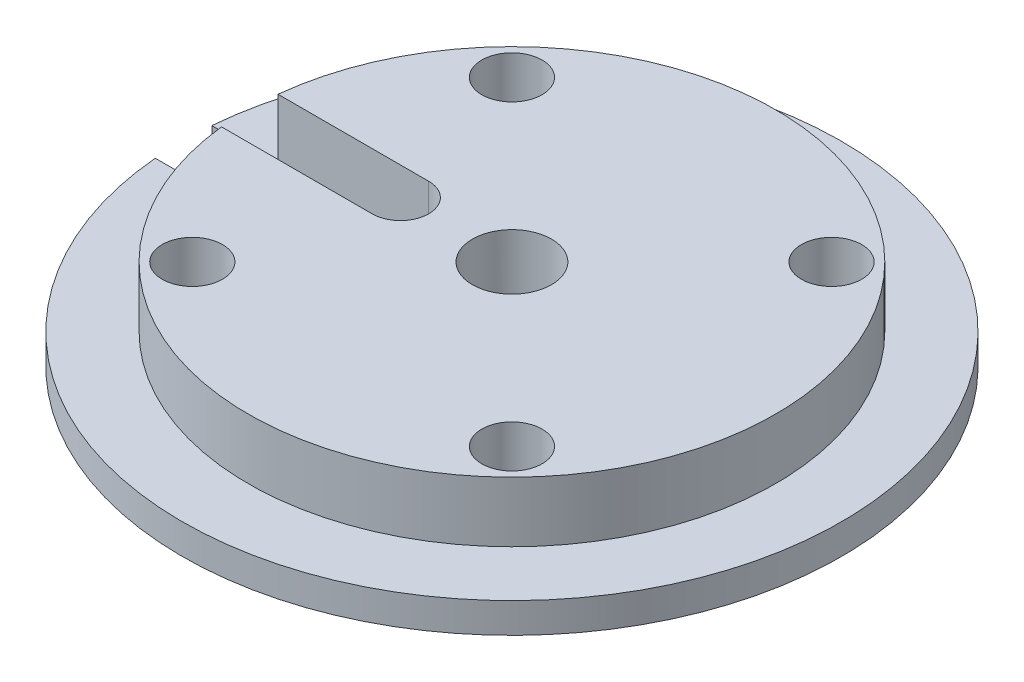
SolidWorks part; units mm, degrees
material "ABS"
ref_plane "正面" through (0, 0, 0) normal (0, 0, 1) x (1, 0, 0)
ref_plane "平面" through (0, 0, 0) normal (0, 1, 0) x (1, 0, 0)
ref_plane "右側面" through (0, 0, 0) normal (1, 0, 0) x (0, 0, -1)
sketch "ｽｹｯﾁ1" plane through (0, 0, 0) normal (0, 1, 0) x (1, 0, 0)
  circle A0 centre (0, 0) radius 2.1
  circle A1 centre (0, 0) radius 14
  dimension "D1" = 28
  dimension "D2" = 4.2
extrude "ﾎﾞｽ - 押し出し1" add sketch "ｽｹｯﾁ1" along normal blind 3.2
sketch "ｽｹｯﾁ2" plane through (0, 3.2, 0) normal (0, 1, 0) x (1, 0, 0)
  line L1 (-13.9194, 1.5) -> (-5.9194, 1.5)
  line L2 (-13.9194, 1.5) -> (-13.9194, -1.5) construction
  line L3 (-13.9194, -1.5) -> (-5.9194, -1.5)
  line L4 (-5.9194, 1.5) -> (-5.9194, -1.5) construction
  circle A0 centre (0, 0) radius 14 construction
  arc A1 (-5.9194, 1.5) -> (-5.9194, -1.5) centre (-5.9194, 0) cw
  arc A2 (-13.9194, 1.5) -> (-13.9194, -1.5) centre (-13.9194, 0) ccw
  dimension "D1" = 3
  dimension "D2" = 8
extrude "ｶｯﾄ - 押し出し1" cut sketch "ｽｹｯﾁ2" against normal blind 10
sketch "ｽｹｯﾁ3" plane through (0, 0, 0) normal (0, -1, 0) x (1, 0, 0)
  line L0 (-17.4356, -1.5) -> (-13.9194, -1.5)
  line L1 (-5.9194, 0) -> (-7.5194, 0) construction
  line L2 (-13.9194, 1.5) -> (-17.4356, 1.5)
  line L5 (-5.9194, -0.8) -> (-7.5194, -0.8)
  line L6 (-5.9194, 0.8) -> (-7.5194, 0.8)
  arc A0 (-17.4356, -1.5) -> (-17.4356, 1.5) centre (0, 0) ccw
  circle A3 centre (0, 0) radius 2.1 construction
  circle A4 centre (0, 0) radius 2.1
  arc A5 (-13.9194, 1.5) -> (-13.9194, -1.5) centre (-13.9194, 0) cw
  arc A6 (-17.4356, 1.5) -> (-17.4356, -1.5) centre (0, 0) ccw construction
  arc A7 (-5.9194, -1.5) -> (-5.9194, 1.5) centre (-5.9194, 0) ccw construction
  arc A8 (-5.9194, -1.5) -> (-5.9194, 1.5) centre (-5.9194, 0) ccw construction
  arc A11 (-5.9194, -0.8) -> (-5.9194, 0.8) centre (-5.9194, 0) ccw
  arc A12 (-7.5194, 0.8) -> (-7.5194, -0.8) centre (-7.5194, 0) ccw
  point P6 (-6.7194, 0)
  dimension "D1" = 35
  dimension "D2" = 0.8
  dimension "D3" = 1.6
extrude "ﾎﾞｽ - 押し出し2" add sketch "ｽｹｯﾁ3" along normal blind 1.6
sketch "ｽｹｯﾁ4" plane through (0, -1.6, 0) normal (0, -1, 0) x (1, 0, 0)
  line L0 (0, 0) -> (-10.0656, -10.0656) construction
  line L1 (-8.4853, 8.4853) -> (0, 0) construction
  line L2 (0, 0) -> (0, -14) construction
  line L3 (55, 0) -> (-55, 0) construction
  circle A0 centre (-8.4853, 8.4853) radius 1.6
  circle A1 centre (8.4853, -8.4853) radius 1.6
  arc A2 (-13.9194, -1.5) -> (-13.9194, 1.5) centre (0, 0) ccw construction
  arc A3 (-13.9194, -1.5) -> (-13.9194, 1.5) centre (0, 0) ccw construction
  circle A4 centre (8.4853, 8.4853) radius 1.6
  circle A5 centre (-8.4853, -8.4853) radius 1.6
  dimension "D1" = 3.2
  dimension "D2" = 12
  dimension "D3" = 315
extrude "ｶｯﾄ - 押し出し2" cut sketch "ｽｹｯﾁ4" against normal through all
